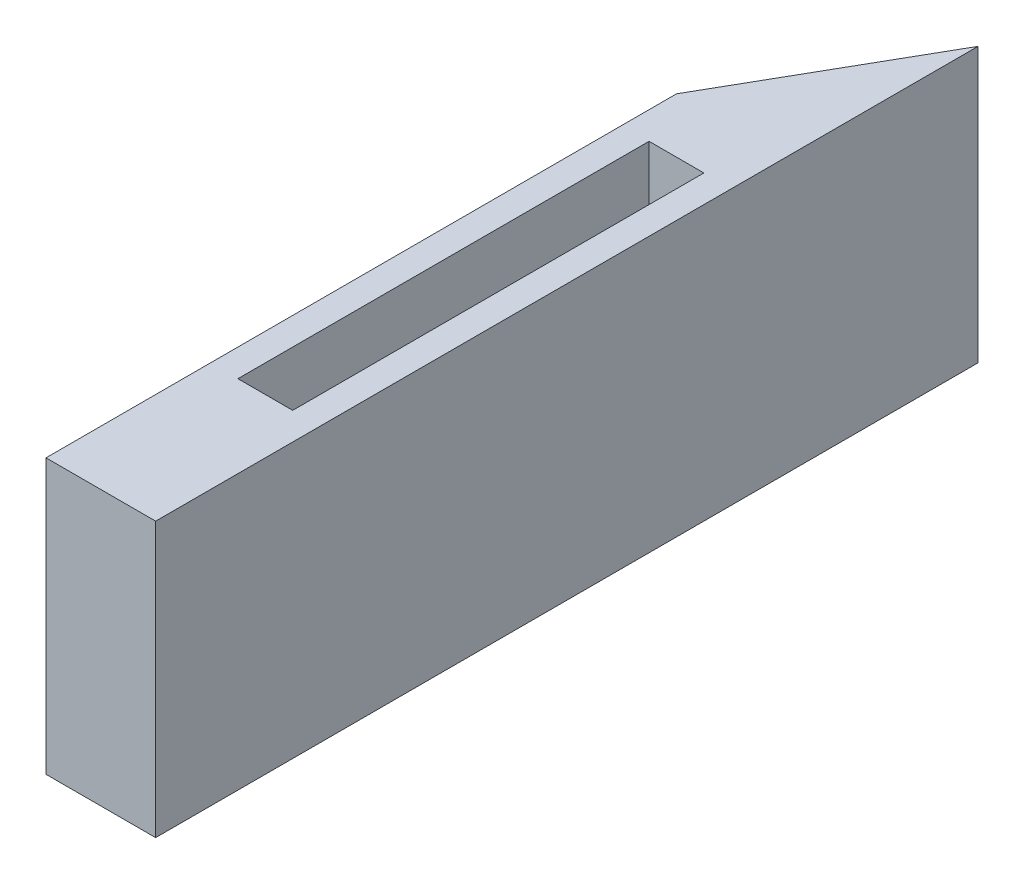
SolidWorks part; units mm, degrees
ref_plane "Спереди" through (0, 0, 0) normal (0, 0, 1) x (1, 0, 0)
ref_plane "Сверху" through (0, 0, 0) normal (0, 1, 0) x (1, 0, 0)
ref_plane "Справа" through (0, 0, 0) normal (1, 0, 0) x (0, 0, -1)
sketch "Эскиз1" plane through (0, 0, 0) normal (1, 0, 0) x (0, 0, -1)
  line L1 (0, 0) -> (30, 0)
  line L2 (0, 0) -> (0, 10)
  line L3 (0, 10) -> (30, 10)
  line L4 (30, 0) -> (30, 10)
  dimension "D1" = 10
  dimension "D2" = 30
extrude "Бобышка-Вытянуть1" add sketch "Эскиз1" along normal blind 4
sketch "Эскиз2" plane through (0, 10, 0) normal (0, 1, 0) x (1, 0, 0)
  line L0 (2, 0) -> (2, 36.0949) construction
  line L1 (4, 0) -> (0, 0) construction
  line L3 (3, 6) -> (1, 6)
  line L4 (3, 6) -> (3, 21)
  line L5 (3, 21) -> (1, 21)
  line L6 (1, 6) -> (1, 21)
  line L7 (3, 6) -> (1, 21) construction
  line L8 (3, 21) -> (1, 6) construction
  point P4 (2, 13.5)
  dimension "D1" = 2
  dimension "D2" = 15
  dimension "D3" = 13.5
extrude "Вырез-Вытянуть1" cut sketch "Эскиз2" against normal through all
sketch "Эскиз3" plane through (0, 10, 0) normal (0, 1, 0) x (1, 0, 0)
  line L0 (0, 30) -> (0, 0) construction
  line L2 (0, 23) -> (0, 30)
  line L3 (0, 30) -> (4, 30)
  line L5 (0, 23) -> (4, 30)
  dimension "D1" = 7
extrude "Вырез-Вытянуть2" cut sketch "Эскиз3" against normal through all
